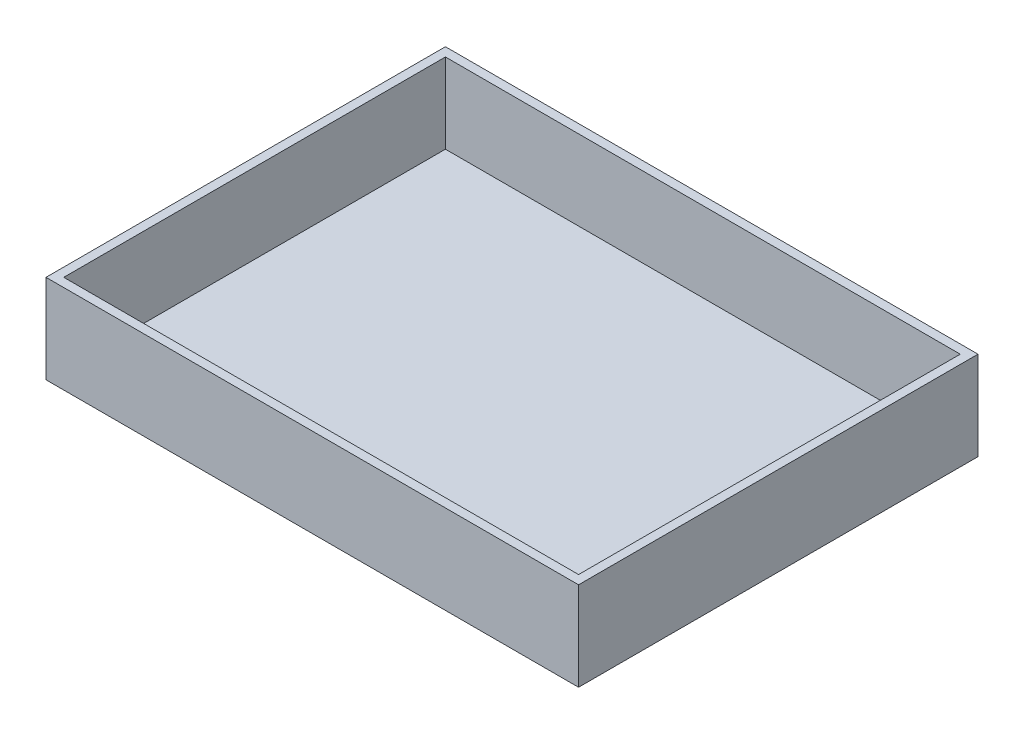
SolidWorks part; units mm, degrees
material "Pino"
ref_plane "Alzado" through (0, 0, 0) normal (0, 0, 1) x (1, 0, 0)
ref_plane "Planta" through (0, 0, 0) normal (0, 1, 0) x (1, 0, 0)
ref_plane "Vista lateral" through (0, 0, 0) normal (1, 0, 0) x (0, 0, -1)
sketch "Croquis1" plane through (0, 0, 0) normal (0, 0, 1) x (1, 0, 0)
  line L1 (0, 0) -> (600, 0)
  line L2 (0, 0) -> (0, -100)
  line L3 (0, -100) -> (600, -100)
  line L4 (600, 0) -> (600, -100)
  dimension "D1" = 100
  dimension "D2" = 600
extrude "Saliente-Extruir1" add sketch "Croquis1" against normal blind 450
sketch "Croquis2" plane through (0, 0, 0) normal (0, 1, 0) x (1, 0, 0)
  line L0 (0, 450) -> (0, 0) construction
  line L1 (10, 10) -> (590, 10)
  line L2 (10, 10) -> (10, 440)
  line L3 (10, 440) -> (590, 440)
  line L4 (590, 10) -> (590, 440)
  line L5 (600, 450) -> (0, 450) construction
  line L6 (600, 450) -> (600, 0) construction
  line L7 (600, 0) -> (0, 0) construction
  dimension "D1" = 10
  dimension "D2" = 10
  dimension "D3" = 10
  dimension "D4" = 10
extrude "Cortar-Extruir1" cut sketch "Croquis2" against normal blind 90
